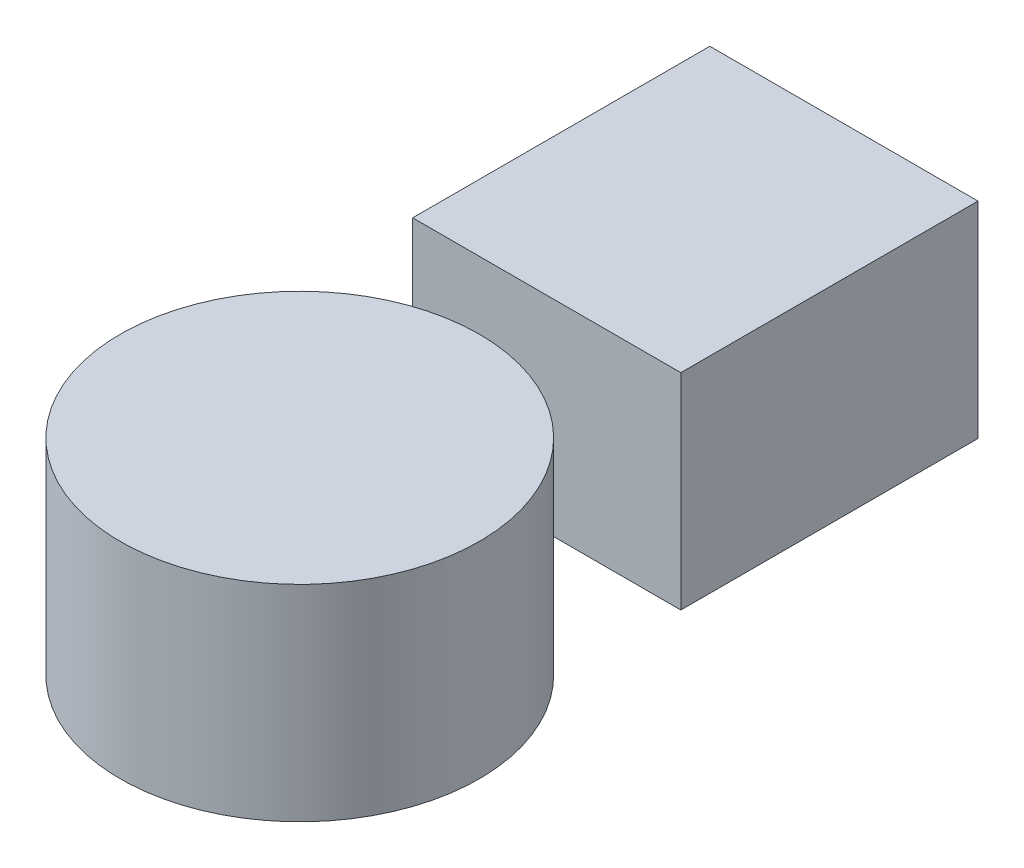
SolidWorks part; units mm, degrees
ref_plane "Front Plane" through (0, 0, 0) normal (0, 0, 1) x (1, 0, 0)
ref_plane "Top Plane" through (0, 0, 0) normal (0, 1, 0) x (1, 0, 0)
ref_plane "Right Plane" through (0, 0, 0) normal (1, 0, 0) x (0, 0, -1)
sketch "Sketch1" plane through (0, 0, 0) normal (0, 0, 1) x (1, 0, 0)
  line L1 (0, 0) -> (58.687, 0)
  line L2 (0, 0) -> (0, 67.2093)
  line L3 (0, 67.2093) -> (58.687, 67.2093)
  line L4 (58.687, 0) -> (58.687, 67.2093)
revolve "Revolve1" add sketch "Sketch1" angle 360 about L2
sketch "Sketch2" plane through (0, 0, 0) normal (0, 1, 0) x (1, 0, 0)
  line L0 (0, 0) -> (0, 80.7292) construction
  line L1 (-43.8303, 177.8668) -> (43.8303, 177.8668)
  line L2 (-43.8303, 177.8668) -> (-43.8303, 80.7292)
  line L3 (-43.8303, 80.7292) -> (43.8303, 80.7292)
  line L4 (43.8303, 177.8668) -> (43.8303, 80.7292)
extrude "Boss-Extrude1" add sketch "Sketch2" along normal up to surface (67.2093 mm away) separate body up to face at (0, 67.2093, -58.687)
